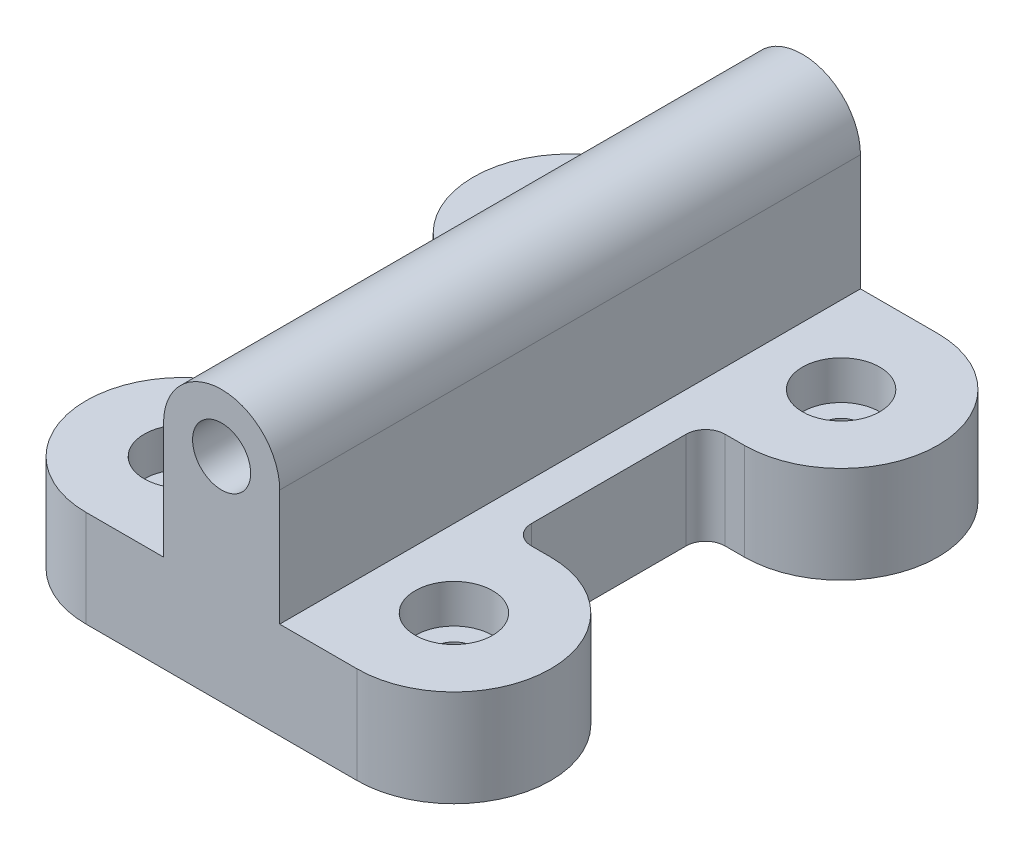
SolidWorks part; units mm, degrees
ref_plane "前视基准面" through (0, 0, 0) normal (0, 0, 1) x (1, 0, 0)
ref_plane "上视基准面" through (0, 0, 0) normal (0, 1, 0) x (1, 0, 0)
ref_plane "右视基准面" through (0, 0, 0) normal (1, 0, 0) x (0, 0, -1)
other "Configuration Table"
sketch "草图1" plane through (0, 0, 0) normal (0, 1, 0) x (1, 0, 0)
  line L0 (-21.8194, 13.4558) -> (-7.8194, 13.4558) construction
  line L1 (-21.8194, 18.4558) -> (-20.8194, 18.4558)
  line L2 (-21.8194, 8.4558) -> (-7.8194, 8.4558)
  line L3 (-19.8194, 19.4558) -> (-19.8194, 27.4558)
  line L5 (-9.8194, 27.4558) -> (-9.8194, 19.4558)
  line L6 (-21.8194, 33.4558) -> (-7.8194, 33.4558) construction
  line L7 (-21.8194, 38.4558) -> (-7.8194, 38.4558)
  line L8 (-21.8194, 28.4558) -> (-20.8194, 28.4558)
  line L9 (-7.8194, 18.4558) -> (-8.8194, 18.4558)
  line L10 (-7.8194, 28.4558) -> (-8.8194, 28.4558)
  arc A0 (-21.8194, 18.4558) -> (-21.8194, 8.4558) centre (-21.8194, 13.4558) ccw
  arc A1 (-7.8194, 8.4558) -> (-7.8194, 18.4558) centre (-7.8194, 13.4558) ccw
  circle A2 centre (-21.8194, 13.4558) radius 1
  circle A3 centre (-7.8194, 13.4558) radius 1
  arc A4 (-21.8194, 38.4558) -> (-21.8194, 28.4558) centre (-21.8194, 33.4558) ccw
  arc A5 (-7.8194, 28.4558) -> (-7.8194, 38.4558) centre (-7.8194, 33.4558) ccw
  arc A6 (-19.8194, 19.4558) -> (-20.8194, 18.4558) centre (-20.8194, 19.4558) cw
  arc A7 (-9.8194, 19.4558) -> (-8.8194, 18.4558) centre (-8.8194, 19.4558) ccw
  arc A8 (-19.8194, 27.4558) -> (-20.8194, 28.4558) centre (-20.8194, 27.4558) ccw
  arc A9 (-9.8194, 27.4558) -> (-8.8194, 28.4558) centre (-8.8194, 27.4558) cw
  circle A10 centre (-21.8194, 33.4558) radius 1
  circle A11 centre (-7.8194, 33.4558) radius 1
  point P2 (-14.8194, 13.4558)
  point P17 (-14.8194, 33.4558)
  point P26 (-9.8194, 18.4558)
  dimension "D2" = 5
  dimension "D3" = 2
  dimension "D4" = 2
  dimension "D5" = 1
  dimension "D9" = 1
  dimension "D7" = 1
  dimension "D8" = 1
  dimension "D10" = 2
  dimension "D11" = 2
  dimension "D1" = 14
  dimension "D6" = 2
  dimension "D12" = 30
  dimension "D13" = 10
extrude "凸台-拉伸1" add sketch "草图1" along normal blind 5
ref_plane "基准面2" through (0, 0, -8.4558) normal (0, 0, 1) x (1, 0, 0)
sketch "草图7" plane through (0, 0, -8.4558) normal (0, 0, 1) x (1, 0, 0)
  line L0 (-21.8194, 5) -> (-7.8194, 5) construction
  line L1 (-17.8194, 5) -> (-11.8194, 5)
  line L3 (-17.8194, 5) -> (-17.8194, 11)
  line L4 (-17.8194, 11) -> (-11.8194, 11)
  line L5 (-11.8194, 11) -> (-11.8194, 5)
  arc A0 (-17.8194, 11) -> (-11.8194, 11) centre (-14.8194, 11) cw
  circle A1 centre (-14.8194, 11) radius 1.5
  point P4 (-7.8194, 5)
  point P6 (-21.8194, 5)
  point P13 (-14.8194, 14)
  dimension "D4" = 6
  dimension "D5" = 3
  dimension "D6" = 3
  dimension "D1" = 6
  dimension "D2" = 4
  dimension "D3" = 9
extrude "凸台-拉伸3" add sketch "草图7" against normal up to surface (30 mm away) contours A1 L4 A0 | A1 L4 L3 L1 L5
sketch "草图8" plane through (0, 5, 0) normal (0, 1, 0) x (1, 0, 0)
  circle A0 centre (-21.8194, 33.4558) radius 2
  circle A1 centre (-7.8194, 33.4558) radius 2
  circle A2 centre (-21.8194, 13.4558) radius 2
  circle A3 centre (-7.8194, 13.4558) radius 2
  dimension "D1" = 4
  dimension "D2" = 4
  dimension "D3" = 4
  dimension "D4" = 4
extrude "切除-拉伸1" cut sketch "草图8" against normal blind 2
